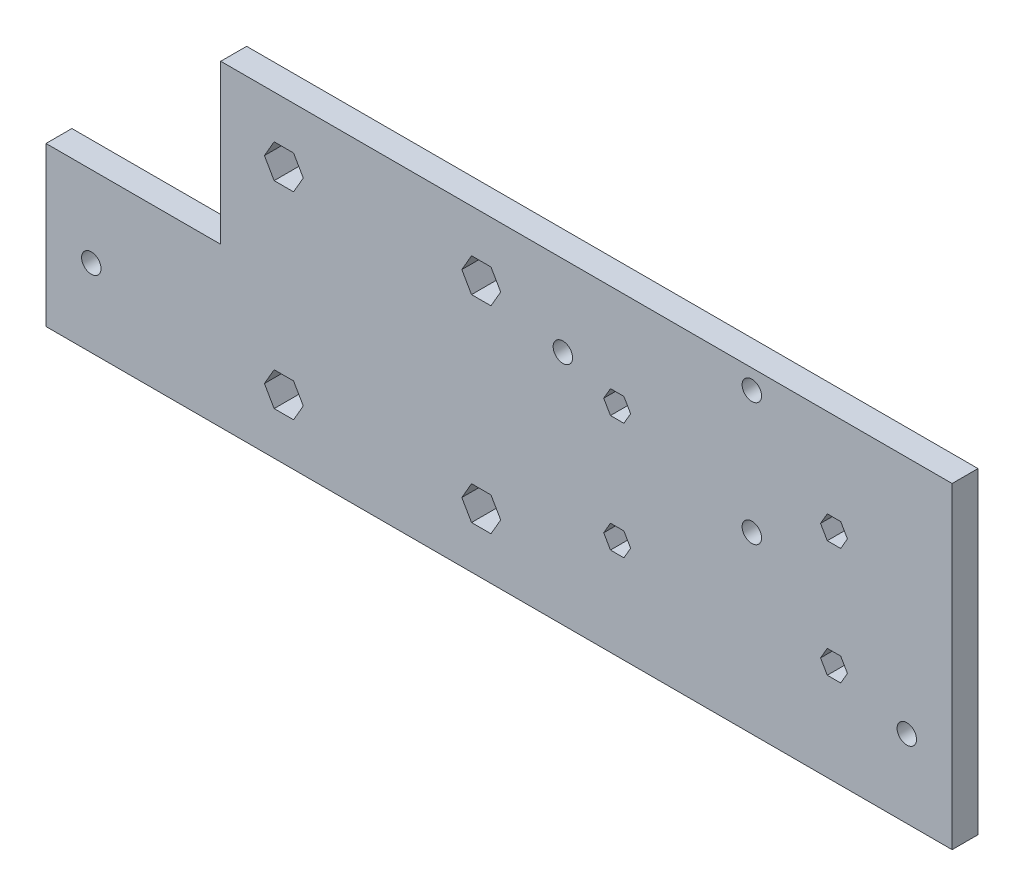
SolidWorks part; units mm, degrees
material "Balsa"
ref_plane "Front Plane" through (0, 0, 0) normal (0, 0, 1) x (1, 0, 0)
ref_plane "Top Plane" through (0, 0, 0) normal (0, 1, 0) x (1, 0, 0)
ref_plane "Right Plane" through (0, 0, 0) normal (1, 0, 0) x (0, 0, -1)
sketch "Sketch1" plane through (0, 0, 0) normal (0, 0, 1) x (1, 0, 0)
  line L0 (0, 0) -> (-40, 0)
  line L1 (0, 0) -> (100, 0)
  line L2 (-13, 24.5) -> (-13, 49)
  line L3 (-13, 49) -> (100, 49)
  line L4 (100, 0) -> (100, 49)
  line L5 (-40, 55) -> (-40, -6) construction
  line L6 (-40, 0) -> (-40, 24.5)
  line L7 (-40, 24.5) -> (-13, 24.5)
  dimension "D1" = 113
  dimension "D2" = 49
extrude "Boss-Extrude1" add sketch "Sketch1" along normal blind 4
sketch "Sketch2" plane through (0, 0, 4) normal (0, 0, 1) x (1, 0, 0)
  circle A0 centre (39.8574, 36.5) radius 1.5
  circle A1 centre (69.0574, 27) radius 1.5
  circle A2 centre (69.0574, 46) radius 1.5
  dimension "D1" = 3
extrude "Cut-Extrude1" cut sketch "Sketch2" against normal blind 4
sketch "Sketch4" plane through (0, 0, -4) normal (0, 0, -1) x (-1, 0, 0)
  line L0 (-100, 24.5) -> (13, 24.5) construction
  line L1 (-80.7108, 31.7) -> (-79.6715, 33.5)
  line L2 (-79.6715, 33.5) -> (-80.7108, 35.3)
  line L3 (-80.7108, 35.3) -> (-82.7892, 35.3)
  line L4 (-82.7892, 35.3) -> (-83.8285, 33.5)
  line L5 (-83.8285, 33.5) -> (-82.7892, 31.7)
  line L6 (-82.7892, 31.7) -> (-80.7108, 31.7)
  line L7 (-47.2108, 31.7) -> (-46.1715, 33.5)
  line L8 (-46.1715, 33.5) -> (-47.2108, 35.3)
  line L9 (-47.2108, 35.3) -> (-49.2892, 35.3)
  line L10 (-49.2892, 35.3) -> (-50.3285, 33.5)
  line L11 (-50.3285, 33.5) -> (-49.2892, 31.7)
  line L12 (-49.2892, 31.7) -> (-47.2108, 31.7)
  line L13 (-47.2108, 13.7) -> (-46.1715, 15.5)
  line L14 (-46.1715, 15.5) -> (-47.2108, 17.3)
  line L15 (-47.2108, 17.3) -> (-49.2892, 17.3)
  line L16 (-49.2892, 17.3) -> (-50.3285, 15.5)
  line L17 (-50.3285, 15.5) -> (-49.2892, 13.7)
  line L18 (-49.2892, 13.7) -> (-47.2108, 13.7)
  line L19 (-80.7108, 13.7) -> (-79.6715, 15.5)
  line L20 (-79.6715, 15.5) -> (-80.7108, 17.3)
  line L21 (-80.7108, 17.3) -> (-82.7892, 17.3)
  line L22 (-82.7892, 17.3) -> (-83.8285, 15.5)
  line L23 (-83.8285, 15.5) -> (-82.7892, 13.7)
  line L24 (-82.7892, 13.7) -> (-80.7108, 13.7)
  line L25 (-100, 0) -> (-100, 49) construction
  circle A0 centre (-48.25, 33.5) radius 1.8 construction
  circle A7 centre (-81.75, 33.5) radius 1.8 construction
  circle A8 centre (-48.25, 15.5) radius 1.8 construction
  circle A9 centre (-81.75, 15.5) radius 1.8 construction
  dimension "D1" = 18
  dimension "D4" = 3.6
  dimension "D2" = 33.5
extrude "Cut-Extrude5" cut sketch "Sketch4" against normal blind 34
sketch "Sketch5" plane through (0, 0, 0) normal (0, 0, -1) x (-1, 0, 0)
  line L0 (-100, 24.5) -> (40, 24.5) construction
  line L1 (-100, 0) -> (-100, 49) construction
  line L3 (4.7511, 37.15) -> (6.2522, 39.75)
  line L4 (6.2522, 39.75) -> (4.7511, 42.35)
  line L5 (4.7511, 42.35) -> (1.7489, 42.35)
  line L6 (1.7489, 42.35) -> (0.2478, 39.75)
  line L7 (0.2478, 39.75) -> (1.7489, 37.15)
  line L8 (1.7489, 37.15) -> (4.7511, 37.15)
  line L9 (-25.7489, 37.15) -> (-24.2478, 39.75)
  line L10 (-24.2478, 39.75) -> (-25.7489, 42.35)
  line L11 (-25.7489, 42.35) -> (-28.7511, 42.35)
  line L12 (-28.7511, 42.35) -> (-30.2522, 39.75)
  line L13 (-30.2522, 39.75) -> (-28.7511, 37.15)
  line L14 (-28.7511, 37.15) -> (-25.7489, 37.15)
  line L15 (-25.7489, 6.65) -> (-24.2478, 9.25)
  line L16 (-24.2478, 9.25) -> (-25.7489, 11.85)
  line L17 (-25.7489, 11.85) -> (-28.7511, 11.85)
  line L18 (-28.7511, 11.85) -> (-30.2522, 9.25)
  line L19 (-30.2522, 9.25) -> (-28.7511, 6.65)
  line L20 (-28.7511, 6.65) -> (-25.7489, 6.65)
  line L21 (4.7511, 6.65) -> (6.2522, 9.25)
  line L22 (6.2522, 9.25) -> (4.7511, 11.85)
  line L23 (4.7511, 11.85) -> (1.7489, 11.85)
  line L24 (1.7489, 11.85) -> (0.2478, 9.25)
  line L25 (0.2478, 9.25) -> (1.7489, 6.65)
  line L26 (1.7489, 6.65) -> (4.7511, 6.65)
  circle A4 centre (3.25, 39.75) radius 2.6 construction
  circle A5 centre (-27.25, 39.75) radius 2.6 construction
  circle A6 centre (-27.25, 9.25) radius 2.6 construction
  circle A7 centre (3.25, 9.25) radius 2.6 construction
  point P1 (5.5017, 38.45)
  dimension "D1" = 5.2
extrude "Cut-Extrude6" cut sketch "Sketch5" against normal blind 34
sketch "Sketch6" plane through (0, 0, 4) normal (0, 0, 1) x (1, 0, 0)
  circle A0 centre (-33, 12) radius 1.5
  circle A1 centre (93, 12) radius 1.5
extrude "Cut-Extrude7" cut sketch "Sketch6" against normal blind 10
